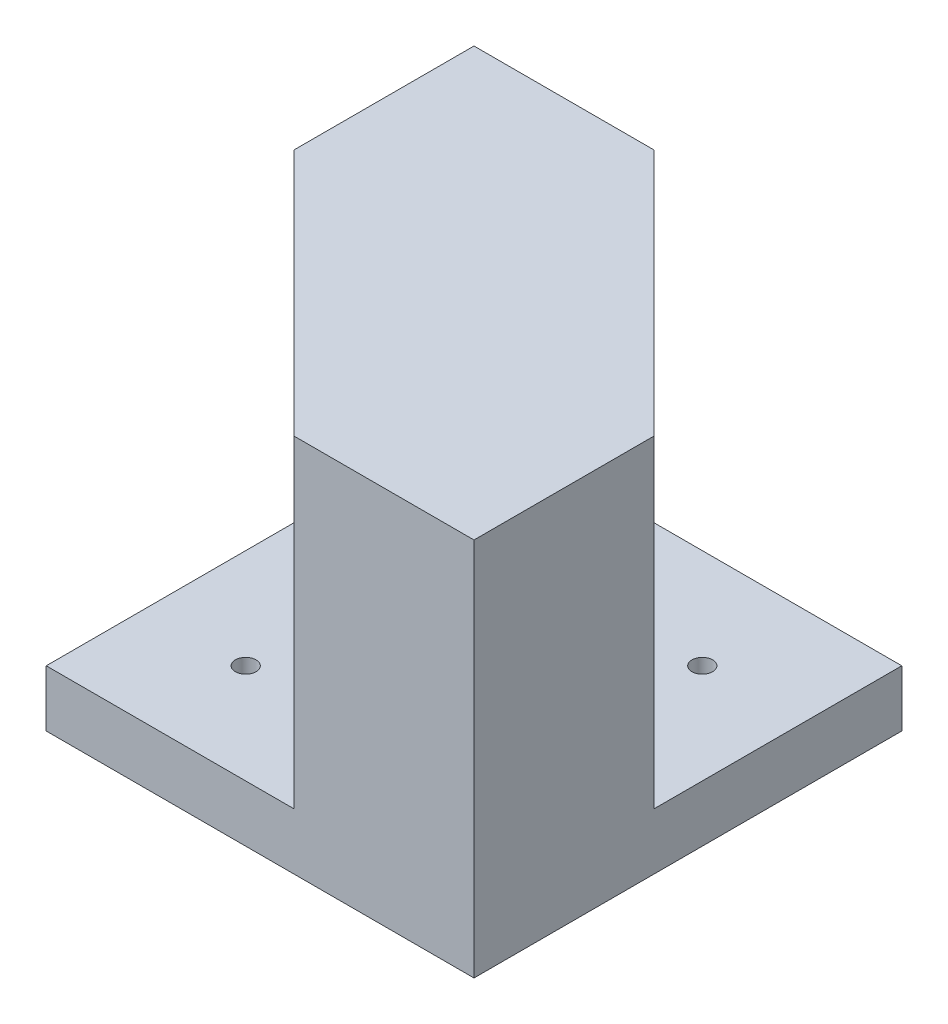
SolidWorks part; units mm, degrees
ref_plane "Front Plane" through (0, 0, 0) normal (0, 0, 1) x (1, 0, 0)
ref_plane "Top Plane" through (0, 0, 0) normal (0, 1, 0) x (1, 0, 0)
ref_plane "Right Plane" through (0, 0, 0) normal (1, 0, 0) x (0, 0, -1)
sketch "Sketch1" plane through (0, 0, 0) normal (0, 1, 0) x (1, 0, 0)
  line L1 (-33.655, 33.655) -> (33.655, 33.655)
  line L2 (-33.655, 33.655) -> (-33.655, -33.655)
  line L3 (-33.655, -33.655) -> (33.655, -33.655)
  line L4 (33.655, 33.655) -> (33.655, -33.655)
  line L5 (-33.655, 33.655) -> (33.655, -33.655) construction
  line L6 (-33.655, -33.655) -> (33.655, 33.655) construction
  circle A0 centre (17.9605, 17.9605) radius 1.625
  circle A2 centre (-17.9605, -17.9605) radius 1.625
  circle A4 centre (-17.9605, 17.9605) radius 1.625 [skipped]
  circle A5 centre (17.9605, -17.9605) radius 1.625 [skipped]
  point P0 (0, 0)
  point P20 (0, 0)
  dimension "D1" = 3.25
  dimension "D2" = 25.4
  dimension "D4" = 67.31
  dimension "D3" = 4
extrude "Boss-Extrude1" add sketch "Sketch1" along normal blind 8.89
sketch "Sketch2" plane through (0, 8.89, 0) normal (0, 1, 0) x (1, 0, 0)
  line L0 (-17.9431, 33.655) -> (33.655, -17.9431)
  line L1 (33.655, -17.9431) -> (33.655, -5.3707)
  line L2 (33.655, -5.3707) -> (-5.3707, 33.655)
  line L3 (-5.3707, 33.655) -> (-17.9431, 33.655)
  line L6 (17.9431, -33.655) -> (-33.655, 17.9431)
  line L8 (33.655, -33.655) -> (33.655, 33.655) construction
  line L9 (33.655, 33.655) -> (-33.655, 33.655) construction
  line L10 (-33.655, -33.655) -> (33.655, -33.655) construction
  line L11 (-33.655, 33.655) -> (-33.655, -33.655) construction
  line L12 (-33.655, 17.9431) -> (-33.655, 5.3707)
  line L13 (-33.655, 5.3707) -> (5.3707, -33.655)
  line L14 (5.3707, -33.655) -> (17.9431, -33.655)
  line L15 (-33.655, 17.9431) -> (-33.655, 33.655)
  line L16 (-33.655, 33.655) -> (-17.9431, 33.655)
  line L17 (17.9431, -33.655) -> (33.655, -33.655)
  line L18 (33.655, -33.655) -> (33.655, -17.9431)
  line M14 (33.655, -33.655) -> (33.655, 33.655)
  line M15 (33.655, 33.655) -> (-33.655, 33.655)
  line M16 (-33.655, 33.655) -> (-33.655, -33.655)
  line M17 (-33.655, -33.655) -> (33.655, -33.655)
  dimension "D1" = 45
  dimension "D2" = 8.89
  dimension "D3" = 8.89
  dimension "D4" = 40
extrude "Boss-Extrude2" add sketch "Sketch2" along normal blind 50.8 contours L13 L6 M16 M17 | L6 L0 M17 M14 M15 M16 | L2 L0 M14 M15
sketch "Sketch3" plane through (-14.1421, 0, 14.1421) normal (-0.7071, 0, 0.7071) x (0.7071, 0, 0.7071)
  line L0 (-17.9605, 52.2505) -> (17.9605, 16.3295) construction
  line L1 (0, 8.89) -> (27.5954, 8.89) construction
  line L2 (0, 0) -> (0, 34.29) construction
  line L3 (0, 34.29) -> (-27.5954, 34.29) construction
  line L4 (-27.5954, 59.69) -> (-27.5954, 8.89) construction
  circle A0 centre (-17.9605, 52.2505) radius 2
  circle A1 centre (17.9605, 16.3295) radius 2
  circle A2 centre (0, 34.29) radius 2
  circle A3 centre (17.9605, 52.2505) radius 2
  circle A4 centre (-17.9605, 16.3295) radius 2
  dimension "4mm" = 4
  dimension "D2" = 45
  dimension "D3" = 50.8
extrude "Cut-Extrude2" cut sketch "Sketch3" against normal blind 127
